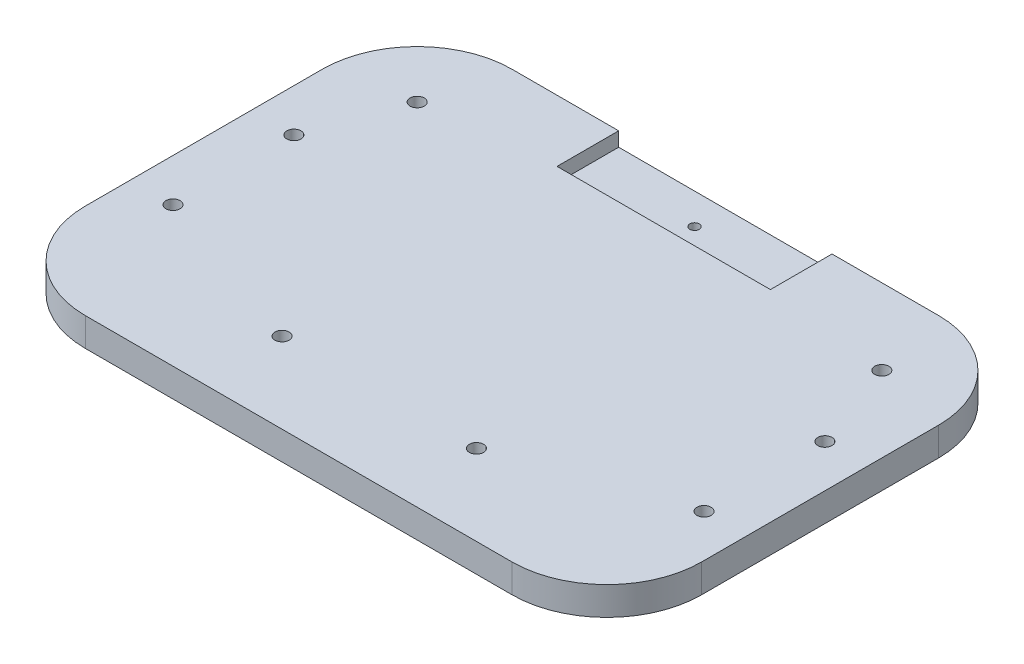
SolidWorks part; units mm, degrees
material "1060 Alloy"
ref_plane "Front Plane" through (0, 0, 0) normal (0, 0, 1) x (1, 0, 0)
ref_plane "Top Plane" through (0, 0, 0) normal (0, 1, 0) x (1, 0, 0)
ref_plane "Right Plane" through (0, 0, 0) normal (1, 0, 0) x (0, 0, -1)
sketch "Sketch2" plane through (0, 0, 0) normal (0, 1, 0) x (1, 0, 0)
  line L1 (-20, 0) -> (-110, 0)
  line L2 (0, 20) -> (0, 70)
  line L3 (-20, 90) -> (-110, 90)
  line L4 (-130, 20) -> (-130, 70)
  arc A0 (0, 70) -> (-20, 90) centre (-20, 70) ccw
  arc A1 (-20, 0) -> (0, 20) centre (-20, 20) ccw
  arc A2 (-110, 0) -> (-130, 20) centre (-110, 20) cw
  arc A3 (-110, 90) -> (-130, 70) centre (-110, 70) ccw
  point P7 (0, 90)
  point P10 (0, 0)
  dimension "D2" = 20
  dimension "D1" = 130
  dimension "D3" = 90
extrude "Boss-Extrude1" add sketch "Sketch2" along normal blind 6
sketch "Sketch3" plane through (0, 6, 0) normal (0, 1, 0) x (1, 0, 0)
  line L0 (-20, 90) -> (-110, 90) construction
  line L1 (-87.5, 90) -> (-42.5, 90)
  line L2 (-87.5, 90) -> (-87.5, 77)
  line L3 (-87.5, 77) -> (-42.5, 77)
  line L4 (-42.5, 90) -> (-42.5, 77)
  line L5 (-65, 90) -> (-65, 77) construction
  line L6 (-65, 0) -> (-65, 90) construction
  line L7 (-110, 0) -> (-20, 0) construction
  dimension "D1" = 13
  dimension "D2" = 45
extrude "Cut-Extrude1" cut sketch "Sketch3" against normal blind 3
sketch "Sketch4" plane through (0, 3, 0) normal (0, 1, 0) x (1, 0, 0)
  line L0 (-65, 77) -> (-65, 90) construction
  line L1 (-87.5, 77) -> (-42.5, 77) construction
  line L2 (-42.5, 90) -> (-87.5, 90) construction
  point P6 (-65, 83.5)
hole_wizard "Ø2.0mm Dowel Hole1" positions "Sketch4" profile "Sketch5" hole size "Ø2.0" standard "ANSI Metric"
sketch "Sketch5" plane through (-65, 3, -83.5) normal (1, 0, 0) x (0, 0, 1)
  line L0 (0, 0) -> (0, 12.6009)
  line L1 (0, 12.6009) -> (1, 12)
  line L2 (1, 12) -> (1, 0)
  line L5 (1, 0) -> (0, 0)
  line L10 (0, 12.6009) -> (-1, 12) construction
  line L11 (0, -6.35) -> (0, 107.95) construction
  dimension "Hole Dia." = 2
  dimension "Hole Depth" = 12
  dimension "Drill Angle" = 118
sketch "Sketch6" plane through (0, 6, 0) normal (0, 1, 0) x (1, 0, 0)
  line L0 (-87.5, 90) -> (-110, 90) construction
  line L1 (-130, 70) -> (-130, 20) construction
  line L2 (0, 20) -> (0, 70) construction
  line L3 (-65, 90) -> (-65, 0) construction
  line L4 (-42.5, 90) -> (-87.5, 90) construction
  line L5 (-110, 0) -> (-20, 0) construction
  point P0 (-114, 74)
  point P1 (-16, 74)
  point P9 (-121, 55)
  point P11 (-9, 55)
  point P15 (-121, 29.5)
  point P17 (-9, 29.5)
  point P56 (-85.5, 17)
  point P58 (-44.5, 17)
  dimension "D1" = 16
  dimension "D2" = 16
  dimension "D3" = 16
  dimension "D4" = 35
  dimension "D5" = 9
  dimension "D6" = 9
  dimension "D7" = 25.5
  dimension "D8" = 17
  dimension "D9" = 20.5
hole_wizard "Ø3.0mm Dowel Hole1" positions "Sketch6" profile "Sketch7" hole size "Ø3.0" standard "ANSI Metric"
sketch "Sketch7" plane through (-114, 6, -74) normal (1, 0, 0) x (0, 0, 1)
  line L0 (0, 0) -> (0, 12.9013)
  line L1 (0, 12.9013) -> (1.5, 12)
  line L2 (1.5, 12) -> (1.5, 0)
  line L5 (1.5, 0) -> (0, 0)
  line L10 (0, 12.9013) -> (-1.5, 12) construction
  line L11 (0, -6.35) -> (0, 107.95) construction
  dimension "Hole Dia." = 3
  dimension "Hole Depth" = 12
  dimension "Drill Angle" = 118
